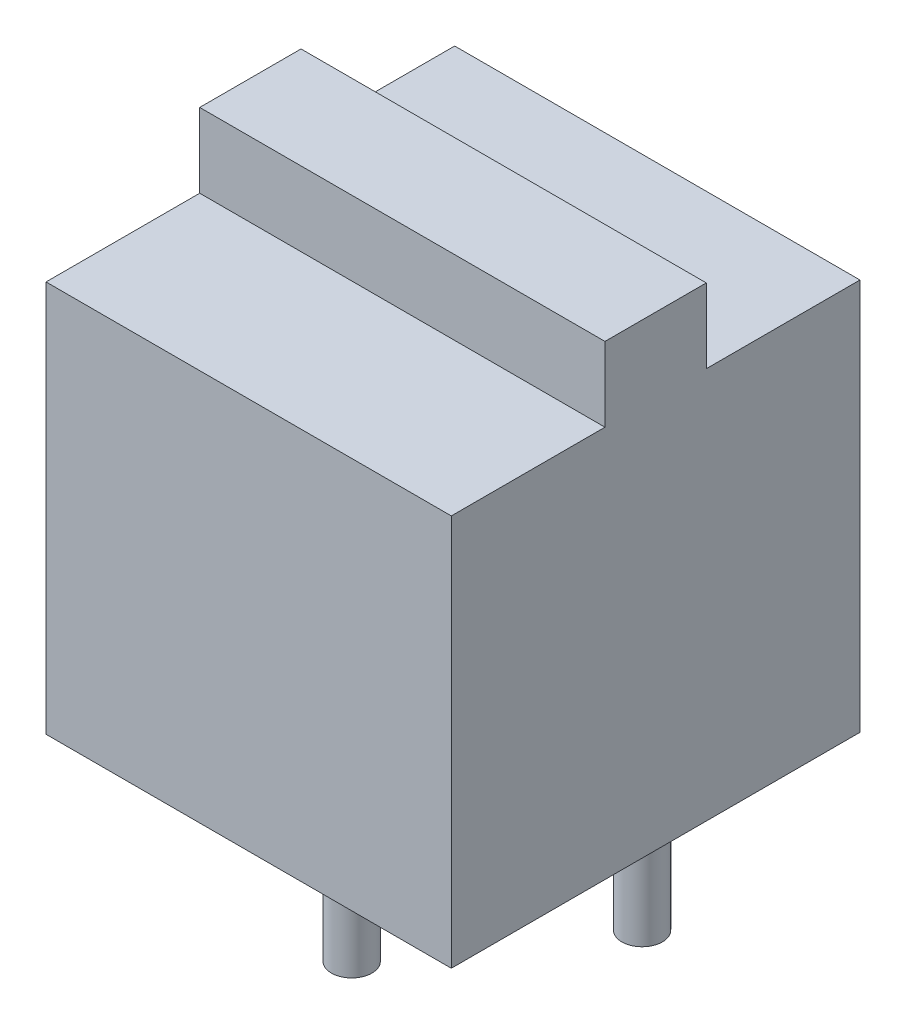
SolidWorks part; units mm, degrees
ref_plane "Alzado" through (0, 0, 0) normal (0, 0, 1) x (1, 0, 0)
ref_plane "Planta" through (0, 0, 0) normal (0, 1, 0) x (1, 0, 0)
ref_plane "Vista lateral" through (0, 0, 0) normal (1, 0, 0) x (0, 0, -1)
sketch "Croquis1" plane through (0, 0, 0) normal (0, 1, 0) x (1, 0, 0)
  line L1 (-6, -6.05) -> (6, -6.05)
  line L2 (-6, -6.05) -> (-6, 6.05)
  line L3 (-6, 6.05) -> (6, 6.05)
  line L4 (6, -6.05) -> (6, 6.05)
  line L5 (-6, -6.05) -> (6, 6.05) construction
  line L6 (-6, 6.05) -> (6, -6.05) construction
  point P0 (0, 0)
  dimension "D1" = 12
  dimension "D2" = 12.1
extrude "Saliente-Extruir1" add sketch "Croquis1" along normal blind 11.6
sketch "Croquis2" plane through (0, 11.6, 0) normal (0, 1, 0) x (1, 0, 0)
  line L0 (6, -6.05) -> (6, 6.05) construction
  line L1 (-6, -1.5) -> (6, -1.5)
  line L2 (-6, -1.5) -> (-6, 1.5)
  line L3 (-6, 1.5) -> (6, 1.5)
  line L4 (6, -1.5) -> (6, 1.5)
  line L5 (-6, -1.5) -> (6, 1.5) construction
  line L6 (-6, 1.5) -> (6, -1.5) construction
  point P0 (0, 0)
  dimension "D1" = 3
extrude "Saliente-Extruir2" add sketch "Croquis2" along normal blind 2.2
sketch "Croquis3" plane through (0, 0, 0) normal (0, -1, 0) x (1, 0, 0)
  line L0 (-6, -6.05) -> (-6, 6.05) construction
  line L1 (-6, 6.05) -> (6, 6.05) construction
  circle A0 centre (-2.75, -1.35) radius 0.6
  circle A1 centre (0.75, 3.75) radius 0.6
  circle A5 centre (4.25, -1.35) radius 0.6
  circle A11 centre (11.25, -1.35) radius 0.6 [skipped]
  circle A12 centre (14.75, 3.75) radius 0.6 [skipped]
  circle A13 centre (18.25, -1.35) radius 0.6 [skipped]
  circle A14 centre (21.75, 3.75) radius 0.6 [skipped]
  circle A15 centre (7.75, 3.75) radius 0.6 [skipped]
  dimension "D1" = 3.25
  dimension "D2" = 3.5
  dimension "D3" = 2.3
  dimension "D4" = 5.1
  dimension "D5" = 1.2
  dimension "D7" = 3.5
  dimension "D6" = 4
extrude "Saliente-Extruir3" add sketch "Croquis3" along normal blind 3.6
